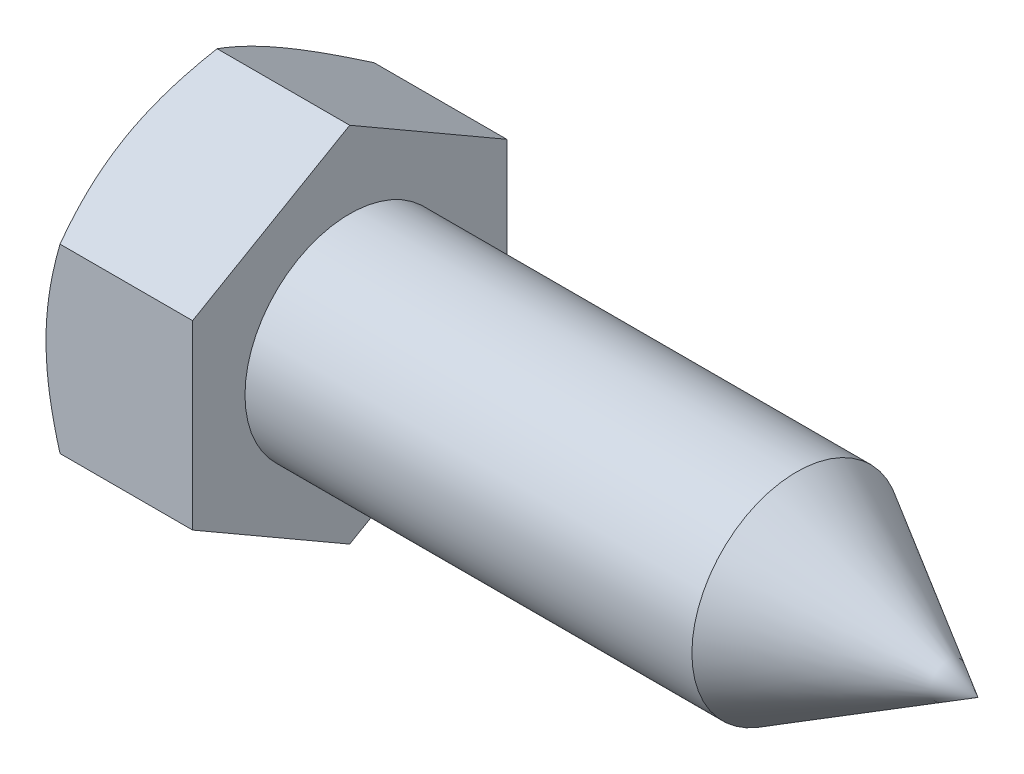
SolidWorks part; units mm, degrees
extrude "BaseHead" add sketch "Sketch1" along normal blind 17.78
sketch "Sketch1" plane through (0, 0, 0) normal (1, 0, 0) x (0, 0, -1)
  line L0 (19.05, 10.9985) -> (19.05, -10.9985)
  line L1 (-19.05, 10.9985) -> (-19.05, -10.9985)
  line L2 (19.05, -10.9985) -> (0, -21.997)
  line L3 (0, -21.997) -> (-19.05, -10.9985)
  line L4 (19.05, 10.9985) -> (0, 21.997)
  line L5 (0, 21.997) -> (-19.05, 10.9985)
  dimension "Width_flats" = 38.1
  dimension "D2" = 120
  dimension "D3" = 19.05
  dimension "D4" = 19.05
  dimension "D5" = 19.05
ref_plane "Plane1" through (0, 0, 0) normal (0, 0, 1) x (1, 0, 0)
ref_plane "Plane2" through (0, 0, 0) normal (0, 1, 0) x (1, 0, 0)
ref_plane "Plane3" through (0, 0, 0) normal (1, 0, 0) x (0, 0, -1)
sketch "Sketch2" plane through (0, 0, 0) normal (0, 0, 1) x (1, 0, 0)
  line L0 (0, 10.9985) -> (0, -10.9985) construction
  line L1 (0, 0) -> (93.98, 0)
  line L2 (0, 0) -> (0, 12.7)
  line L3 (0, 12.7) -> (71.983, 12.7)
  line L4 (93.98, 0) -> (71.983, -12.7) construction
  line L6 (93.98, 0) -> (71.983, 12.7)
  line L7 (0, 0) -> (120.65, 0) construction
  line L8 (0, -12.7) -> (71.983, -12.7) construction
  line L9 (17.78, 21.997) -> (17.78, 10.9985) construction
  dimension "Length" = 76.2
  dimension "Diameter" = 25.4
  dimension "Point_ang" = 60
revolve "BaseBody" add sketch "Sketch2" angle 360 about L7
sketch "Sketch3" plane through (0, 0, 0) normal (0, 0, 1) x (1, 0, 0)
  line L0 (0, 19.05) -> (5.3677, 28.347)
  line L1 (0, 21.997) -> (0, 10.9985) construction
  line L2 (5.3677, 28.347) -> (5.3677, 34.697)
  line L3 (5.3677, 34.697) -> (-12.7, 34.697)
  line L4 (-12.7, 34.697) -> (-12.7, 19.05)
  line L5 (-12.7, 19.05) -> (0, 19.05)
  line L6 (0, 0) -> (99.06, 0) construction
  line L7 (17.78, 21.997) -> (0, 21.997) construction
  dimension "D1" = 19.05
  dimension "D2" = 6.35
  dimension "D3" = 12.7
  dimension "D4" = 6.35
  dimension "Head_ch_ang" = 30
revolve "HeadChamfer" cut sketch "Sketch3" angle 360 about L6
fillet "HeadFillet" [suppressed] radius 2.286
equation "\"D3@Sketch1\" = \"Width_flats@Sketch1\" / 2"
equation "\"D4@Sketch1\" = \"D3@Sketch1\""
equation "\"D5@Sketch1\" = \"D4@Sketch1\""
equation "\"D1@Sketch3\" = \"Width_flats@Sketch1\" / 2"
